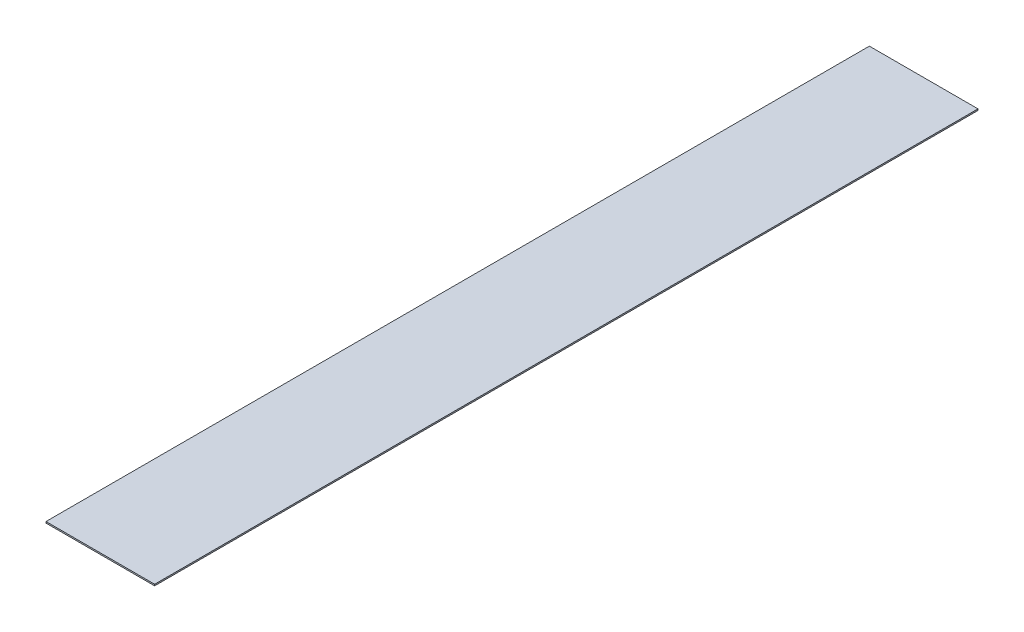
SolidWorks part; units mm, degrees
material "Pine"
ref_plane "Front Plane" through (0, 0, 0) normal (0, 0, 1) x (1, 0, 0)
ref_plane "Top Plane" through (0, 0, 0) normal (0, 1, 0) x (1, 0, 0)
ref_plane "Right Plane" through (0, 0, 0) normal (1, 0, 0) x (0, 0, -1)
sketch "Sketch1" plane through (0, 0, 0) normal (0, 0, 1) x (1, 0, 0)
  line L1 (120.65, -1.5875) -> (-120.65, -1.5875)
  line L2 (120.65, -1.5875) -> (120.65, 1.5875)
  line L3 (120.65, 1.5875) -> (-120.65, 1.5875)
  line L4 (-120.65, -1.5875) -> (-120.65, 1.5875)
  line L5 (120.65, -1.5875) -> (-120.65, 1.5875) construction
  line L6 (120.65, 1.5875) -> (-120.65, -1.5875) construction
  point P0 (0, 0)
  dimension "D1" = 3.175
  dimension "D2" = 241.3
extrude "Boss-Extrude1" add sketch "Sketch1" along normal blind 1828.8
